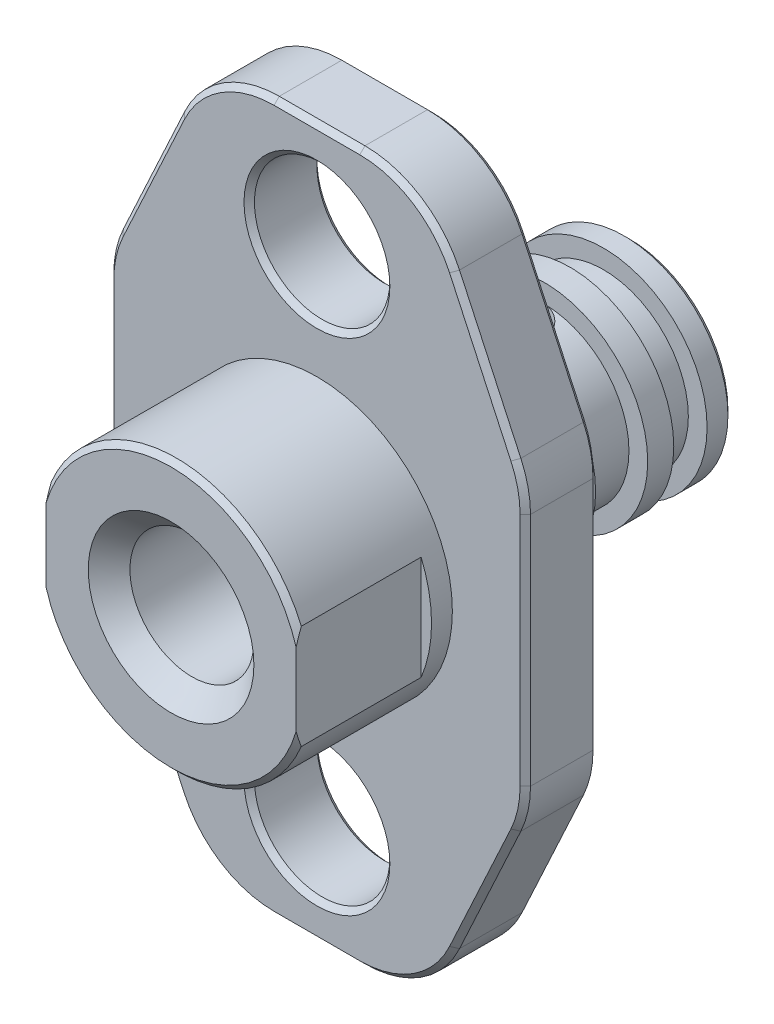
SolidWorks part; units mm, degrees
material "316 S/Steel"
ref_plane "Front" through (0, 0, 0) normal (0, 0, 1) x (1, 0, 0)
ref_plane "Top" through (0, 0, 0) normal (0, 1, 0) x (1, 0, 0)
ref_plane "Right" through (0, 0, 0) normal (1, 0, 0) x (0, 0, -1)
sketch "Sketch1" plane through (0, 0, 0) normal (1, 0, 0) x (0, 0, -1)
  line L0 (0, 0) -> (44, 0) construction
  line L1 (14, 13) -> (0.5, 13)
  line L2 (0.5, 13) -> (0, 12.5)
  line L3 (14, 13) -> (14, 35)
  line L4 (14, 35) -> (21, 35)
  line L5 (21, 35) -> (21, 9.95)
  line L6 (21, 9.95) -> (25.1, 9.95)
  line L7 (25.1, 9.95) -> (25.1, 8.15)
  line L8 (25.1, 8.15) -> (28.3, 8.15)
  line L9 (28.3, 8.15) -> (28.3, 9.95)
  line L10 (28.3, 9.95) -> (30.8, 9.95)
  line L11 (30.8, 9.95) -> (30.8, 8.15)
  line L12 (30.8, 8.15) -> (35.8, 8.15)
  line L13 (35.8, 8.15) -> (35.8, 9.95)
  line L14 (35.8, 9.95) -> (38.3, 9.95)
  line L15 (38.3, 9.95) -> (38.3, 8.15)
  line L16 (38.3, 8.15) -> (41.5, 8.15)
  line L17 (41.5, 8.15) -> (41.5, 9.95)
  line L18 (41.5, 9.95) -> (43.5, 9.95)
  line L19 (43.5, 9.95) -> (44, 9.45)
  line L20 (44, 9.45) -> (44, 0)
  line L21 (0, 12.5) -> (0, 7.95)
  line L22 (2, 5.95) -> (19, 5.95)
  line L23 (20.1717, 4) -> (38, 4)
  line L24 (19, 5.95) -> (20.1717, 4)
  line L25 (38, 4) -> (40.4034, 0)
  line L26 (40.4034, 0) -> (44, 0)
  line L27 (0, 4) -> (44, 4) construction
  line L28 (0, 5.95) -> (44, 5.95) construction
  line L29 (0, 7.95) -> (2, 5.95)
  dimension "D1" = 44
  dimension "D2" = 13
  dimension "D3" = 9.95
  dimension "D4" = 8.15
  dimension "D5" = 14
  dimension "D6" = 7
  dimension "D7" = 35
  dimension "D8" = 4.1
  dimension "D9" = 3.2
  dimension "D10" = 2.5
  dimension "D11" = 5
  dimension "D12" = 2.5
  dimension "D13" = 3.2
  dimension "D14" = 2.5
  dimension "D15" = 45
  dimension "D16" = 0.5
  dimension "D17" = 45
  dimension "D18" = 0.5
  dimension "D19" = 19
  dimension "D20" = 5.95
  dimension "D21" = 4
  dimension "D22" = 59
  dimension "D23" = 38
  dimension "D24" = 59
  dimension "D25" = 2
  dimension "D26" = 45
revolve "Revolve1" add sketch "Sketch1" angle 360 about L0
cosmetic thread "Cosmetic Thread1" parameters "D2"=14.2875
sketch "Sketch3" plane through (0, 0, 0) normal (0, 0, 1) x (1, 0, 0)
  line L0 (0, 34) -> (0, -34) construction
  line L1 (-20, 0) -> (20, 0) construction
  line L2 (-20, 11.2955) -> (-20, -11.2955)
  line L3 (13.1857, 28.2046) -> (19.0731, 15.5001)
  line L4 (20, 11.2955) -> (20, -11.2955)
  line L5 (-4.1126, 34) -> (4.1126, 34)
  line L6 (-13.1857, 28.2046) -> (-19.0731, 15.5001)
  line L7 (13.1857, -28.2046) -> (19.0731, -15.5001)
  line L8 (-20, 34) -> (-20, -34) construction
  line L9 (-20, 34) -> (20, 34) construction
  line L10 (-4.1126, -34) -> (4.1126, -34)
  line L11 (-13.1857, -28.2046) -> (-19.0731, -15.5001)
  arc A0 (-13.1857, 28.2046) -> (-4.1126, 34) centre (-4.1126, 24) cw
  arc A1 (-19.0731, 15.5001) -> (-20, 11.2955) centre (-10, 11.2955) ccw
  arc A2 (13.1857, 28.2046) -> (4.1126, 34) centre (4.1126, 24) ccw
  arc A3 (19.0731, 15.5001) -> (20, 11.2955) centre (10, 11.2955) cw
  arc A4 (19.0731, -15.5001) -> (20, -11.2955) centre (10, -11.2955) ccw
  arc A5 (13.1857, -28.2046) -> (4.1126, -34) centre (4.1126, -24) cw
  arc A6 (-13.1857, -28.2046) -> (-4.1126, -34) centre (-4.1126, -24) ccw
  arc A7 (-19.0731, -15.5001) -> (-20, -11.2955) centre (-10, -11.2955) cw
  circle A8 centre (0, 24) radius 6.5
  circle A9 centre (0, -24) radius 6.5
  point P7 (0, 0)
  point P11 (0, 0)
  point P14 (20, -34)
  point P19 (-10.5, 34)
  point P22 (-20, 13.5)
  dimension "D5" = 10
  dimension "D6" = 13
  dimension "D1" = 40
  dimension "D2" = 68
  dimension "D3" = 13.5
  dimension "D4" = 10.5
  dimension "D7" = 24
extrude "Cut-Extrude1" cut sketch "Sketch3" against normal blind 21 flip side to cut
sketch "Sketch4" plane through (0, 0, 0) normal (1, 0, 0) x (0, 0, -1)
  line L0 (33.3, 12.4096) -> (33.3, -12.4096)
  line L1 (35.8, 12.4096) -> (35.8, -12.4096)
  line L2 (33.3, 12.4096) -> (35.8, 12.4096)
  line L3 (33.3, -12.4096) -> (35.8, -12.4096)
  line L4 (44, -9.45) -> (44, 9.45) construction
  point P3 (33.3, 0)
  dimension "D1" = 10.7
  dimension "D2" = 2.5
revolve "Cut-Revolve1" cut sketch "Sketch4" angle 360 about L0
sketch "Sketch7" plane through (0, 0, 0) normal (0, 0, 1) x (1, 0, 0)
  line L0 (0, 0) -> (-12, 0) construction
  line L2 (-12, 6.6844) -> (-14.3589, 6.6844)
  line L3 (-14.3589, 6.6844) -> (-14.3589, -8.3156)
  line L4 (-14.3589, -8.3156) -> (-12, -8.3156)
  line L6 (-12, 6.6844) -> (-12, -8.3156)
  dimension "D1" = 12
  dimension "D2" = 15
extrude "Cut-Extrude2" cut sketch "Sketch7" against normal blind 12
pattern_circular "CirPattern1" count 2 over 180 about axis through (0, 0, -12) along (0, 1, 0) of "Cut-Extrude2"
chamfer "Chamfer1" distance 0.5 angle 45 36 edges at (-6.5, 24, -14) (6.5, 24, -21) (-6.5, -24, -14) (-6.5, -24, -21) (-9.4956, 32.4275, -14) (0, 34, -14) (-16.1294, 21.8524, -14) (9.4956, 32.4275, -14) (-19.7655, 13.4483, -14) (16.1294, 21.8524, -14) (-20, 0, -14) (19.7655, 13.4483, -14) (-19.7655, -13.4483, -14) (20, 0, -14) (-16.1294, -21.8524, -14) (19.7655, -13.4483, -14) (-9.4956, -32.4275, -14) (16.1294, -21.8524, -14) (0, -34, -14) (9.4956, -32.4275, -14) (-16.1294, 21.8524, -21) (-19.7655, 13.4483, -21) (-9.4956, 32.4275, -21) (-20, 0, -21) (0, 34, -21) (-19.7655, -13.4483, -21) (9.4956, 32.4275, -21) (-16.1294, -21.8524, -21) (16.1294, 21.8524, -21) (-9.4956, -32.4275, -21) (19.7655, 13.4483, -21) (0, -34, -21) (20, 0, -21) (9.4956, -32.4275, -21) (19.7655, -13.4483, -21) (16.1294, -21.8524, -21)
